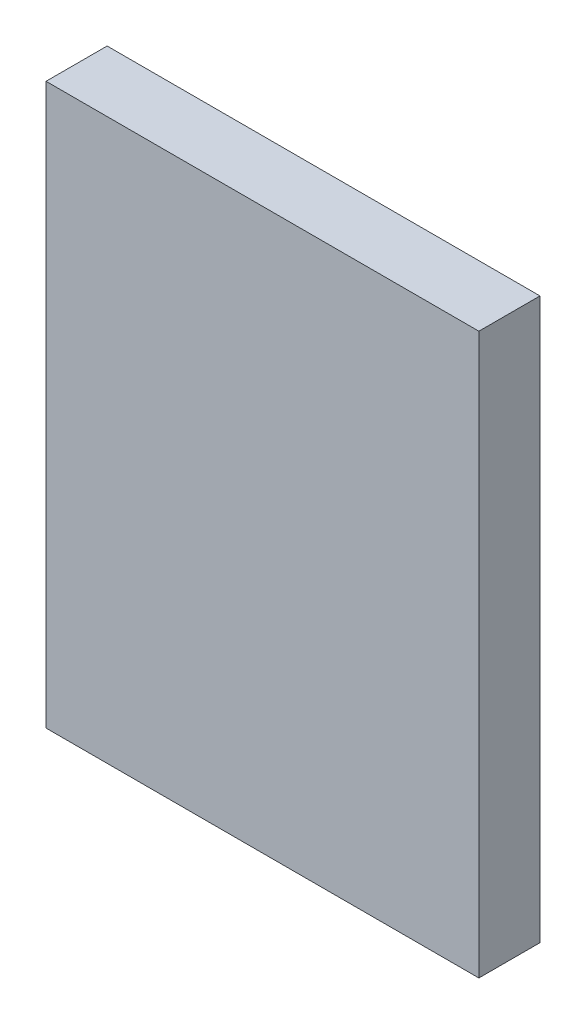
SolidWorks part; units mm, degrees
ref_plane "Front Plane" through (0, 0, 0) normal (0, 0, 1) x (1, 0, 0)
ref_plane "Top Plane" through (0, 0, 0) normal (0, 1, 0) x (1, 0, 0)
ref_plane "Right Plane" through (0, 0, 0) normal (1, 0, 0) x (0, 0, -1)
sketch "Sketch1" plane through (0, 0, 0) normal (0, 0, 1) x (1, 0, 0)
  line L0 (0, 0) -> (17, 0)
  line L1 (17, 0) -> (17, 22)
  line L2 (17, 22) -> (0, 22)
  line L3 (0, 22) -> (0, 0)
extrude "Boss-Extrude1" add sketch "Sketch1" along normal blind 2.4
